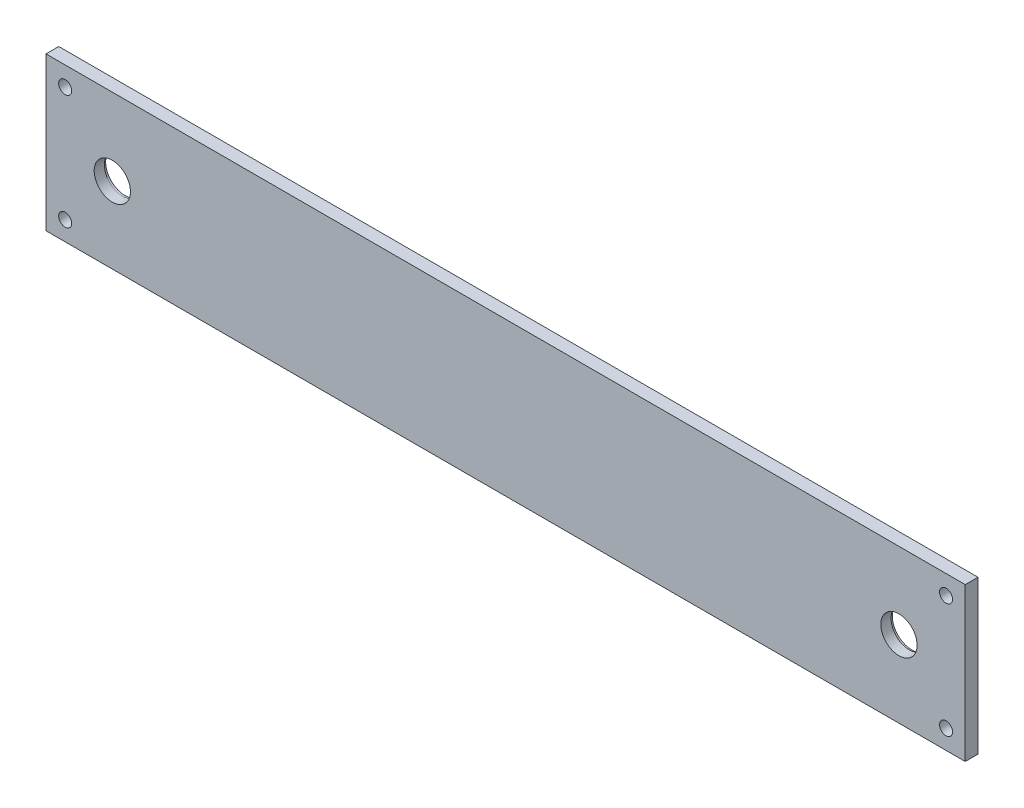
SolidWorks part; units mm, degrees
ref_plane "Front Plane" through (0, 0, 0) normal (0, 0, 1) x (1, 0, 0)
ref_plane "Top Plane" through (0, 0, 0) normal (0, 1, 0) x (1, 0, 0)
ref_plane "Right Plane" through (0, 0, 0) normal (1, 0, 0) x (0, 0, -1)
sketch "Sketch1" plane through (0, 0, 0) normal (0, 0, 1) x (1, 0, 0)
  line L1 (25.9587, -30) -> (-334.0413, -30)
  line L2 (25.9587, -30) -> (25.9587, 30)
  line L3 (25.9587, 30) -> (-334.0413, 30)
  line L4 (-334.0413, -30) -> (-334.0413, 30)
  line L8 (-154.0413, -30) -> (-154.0413, 30) construction
  circle A1 centre (0, 0) radius 7.1
  circle A2 centre (-308.0826, -0.2) radius 7.1
  point P4 (25.9587, 0)
  dimension "D1" = 14.2
  dimension "D2" = 14.2
  dimension "D3" = 360
  dimension "D4" = 25.9587
  dimension "D5" = 25.9587
  dimension "D6" = 308.0826
  dimension "D7" = 60
extrude "Boss-Extrude1" add sketch "Sketch1" against normal blind 4
sketch "Sketch2" plane through (0, 0, -4) normal (0, 0, -1) x (-1, 0, 0)
  line L0 (154.0413, -30) -> (154.0413, 30) construction
  line L4 (-25.9587, 30) -> (-25.9587, -30)
  line L5 (-25.9587, -30) -> (334.0413, -30)
  line L6 (334.0413, -30) -> (334.0413, 30)
  line L7 (334.0413, 30) -> (-25.9587, 30)
  line L8 (-25.9587, 30) -> (-25.9587, -30)
  line L9 (-25.9587, -30) -> (334.0413, -30)
  line L10 (334.0413, -30) -> (334.0413, 30)
  line L11 (334.0413, 30) -> (-25.9587, 30)
  circle A4 centre (0, 0) radius 7.1 construction
  circle A5 centre (0, 0) radius 7.1
  circle A6 centre (0, 0) radius 7.6
  circle A7 centre (308.0826, 0) radius 7.6
  circle A8 centre (308.0826, 0) radius 7.1
  line M5 (-25.9587, 30) -> (-25.9587, -30)
  line M6 (-25.9587, -30) -> (334.0413, -30)
  line M7 (334.0413, -30) -> (334.0413, 30)
  line M8 (334.0413, 30) -> (-25.9587, 30)
  circle M10 centre (308.0826, -0.2) radius 7.1
  dimension "D1" = 0
  dimension "D2" = 15.2
extrude "Boss-Extrude2" add sketch "Sketch2" along normal blind 1 contours A7 A8 M10 | L0 L9 A7 M7 M8 | L0 L11 A6 M6 M5
sketch "Sketch3" plane through (0, 0, -5) normal (0, 0, -1) x (-1, 0, 0)
  line L0 (334.0413, 30) -> (-25.9587, 30) construction
  line L1 (-25.9587, -30) -> (334.0413, -30) construction
  line L2 (308.0826, -27.75) -> (308.0826, -30) construction
  line L3 (308.0826, -27.75) -> (310.3326, -27.75) construction
  line L4 (308.0826, -27.75) -> (309.6735, -29.341) construction
  line L5 (308.0826, -27.75) -> (306.4916, -26.159) construction
  line L6 (319.0266, -14.9853) -> (334.0413, -30) construction
  line L7 (326.5339, -22.4927) -> (322.9984, -26.0282) construction
  line L8 (326.5339, -22.4927) -> (330.0695, -18.9571) construction
  line L9 (334.0413, 0) -> (-25.9587, 0) construction
  line L10 (334.0413, -30) -> (334.0413, 30) construction
  line L11 (-25.9587, 30) -> (-25.9587, -30) construction
  line L12 (154.0413, -30) -> (154.0413, 30) construction
  line L13 (326.5339, 22.4927) -> (330.0695, 18.9571) construction
  line L14 (326.5339, 22.4927) -> (322.9984, 26.0282) construction
  line L15 (-18.4514, 22.4927) -> (-14.9158, 26.0282) construction
  line L16 (-18.4514, 22.4927) -> (-21.9869, 18.9571) construction
  line L17 (-18.4514, -22.4927) -> (-21.9869, -18.9571) construction
  line L18 (-18.4514, -22.4927) -> (-14.9158, -26.0282) construction
  line L19 (-10.944, -14.9853) -> (-25.9587, -30) construction
  line L20 (0, -27.75) -> (1.591, -26.159) construction
  line L21 (0, -27.75) -> (-1.591, -29.341) construction
  line L22 (0, -27.75) -> (-2.25, -27.75) construction
  line L23 (0, -27.75) -> (0, -30) construction
  circle A0 centre (326.5339, -22.4927) radius 2.55
  circle A1 centre (308.0826, -27.75) radius 2.25
  circle A2 centre (308.0826, 0) radius 7.6 construction
  circle A3 centre (308.0826, 0) radius 7.6 construction
  circle A4 centre (308.0826, 27.75) radius 2.25
  arc A5 (309.6735, -29.341) -> (309.6735, 29.341) centre (280.3326, 0) ccw
  arc A6 (306.4916, -26.159) -> (306.4916, 26.159) centre (280.3326, 0) ccw
  circle A7 centre (326.5339, -22.4927) radius 5
  arc A8 (309.6735, -29.341) -> (322.9984, -26.0282) centre (319.0885, -38.756) cw
  arc A9 (330.0695, -18.9571) -> (330.0695, 18.9571) centre (347.7482, 0) cw
  arc A10 (309.6735, 29.341) -> (322.9984, 26.0282) centre (319.0885, 38.756) ccw
  circle A11 centre (326.5339, 22.4927) radius 5
  circle A12 centre (326.5339, 22.4927) radius 2.55
  circle A13 centre (0, 0) radius 7.6 construction
  circle A14 centre (-18.4514, 22.4927) radius 2.55
  circle A15 centre (-18.4514, 22.4927) radius 5
  arc A16 (-1.591, 29.341) -> (-14.9158, 26.0282) centre (-11.006, 38.756) cw
  arc A17 (-21.9869, -18.9571) -> (-21.9869, 18.9571) centre (-39.6657, 0) ccw
  arc A18 (-1.591, -29.341) -> (-14.9158, -26.0282) centre (-11.006, -38.756) ccw
  circle A19 centre (-18.4514, -22.4927) radius 5
  arc A20 (1.591, -26.159) -> (1.591, 26.159) centre (27.75, 0) cw
  arc A21 (-1.591, -29.341) -> (-1.591, 29.341) centre (27.75, 0) cw
  circle A22 centre (0, 27.75) radius 2.25
  circle A23 centre (0, -27.75) radius 2.25
  circle A24 centre (-18.4514, -22.4927) radius 2.55
  dimension "D1" = 5.1
  dimension "D2" = 4.5
  dimension "D4" = 45
  dimension "D5" = 45
  dimension "D6" = 10
extrude "Cut-Extrude1" cut sketch "Sketch3" against normal up to next contours A0 | A12 | A24 | A14
equation "\"D4@Sketch1\"=(\"D3@Sketch1\"-\"D6@Sketch1\")/2"
